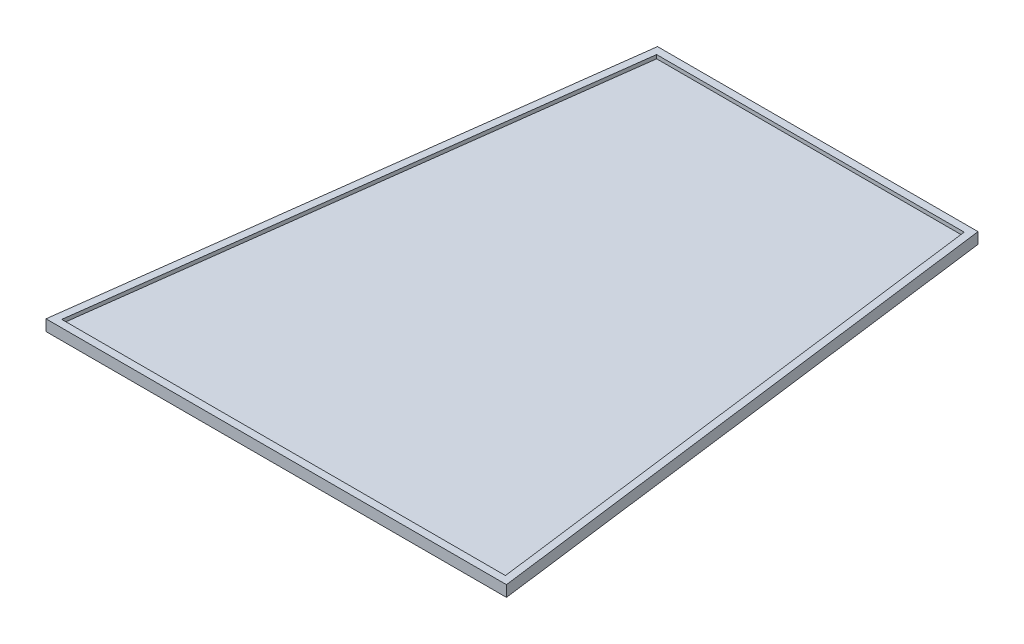
SolidWorks part; units mm, degrees
ref_plane "前视基准面" through (0, 0, 0) normal (0, 0, 1) x (1, 0, 0)
ref_plane "上视基准面" through (0, 0, 0) normal (0, 1, 0) x (1, 0, 0)
ref_plane "右视基准面" through (0, 0, 0) normal (1, 0, 0) x (0, 0, -1)
other "Configuration Table"
sketch "草图1" plane through (0, 0, 0) normal (0, 1, 0) x (1, 0, 0)
  line L0 (-31.25, 0) -> (31.25, 0)
  line L1 (31.25, 0) -> (21.75, 73.5)
  line L2 (21.75, 73.5) -> (-21.75, 73.5)
  line L3 (-21.75, 73.5) -> (-31.25, 0)
  point P3 (0, 73.5)
  dimension "D1" = 73.5
  dimension "D2" = 43.5
  dimension "D3" = 62.5
extrude "凸台-拉伸1" add sketch "草图1" along normal blind 1
sketch "草图2" plane through (0, 1, 0) normal (0, 1, 0) x (1, 0, 0)
  line L0 (-20.8709, 72.5) -> (-30.1124, 1)
  line L1 (-30.1124, 1) -> (30.1124, 1)
  line L2 (30.1124, 1) -> (20.8709, 72.5)
  line L3 (20.8709, 72.5) -> (-20.8709, 72.5)
  line L4 (-21.75, 73.5) -> (-31.25, 0)
  line L5 (-31.25, 0) -> (31.25, 0)
  line L6 (31.25, 0) -> (21.75, 73.5)
  line L7 (21.75, 73.5) -> (-21.75, 73.5)
  line L8 (-21.75, 73.5) -> (-31.25, 0)
  line L9 (-31.25, 0) -> (31.25, 0)
  line L10 (31.25, 0) -> (21.75, 73.5)
  line L11 (21.75, 73.5) -> (-21.75, 73.5)
  dimension "D1" = 0
  dimension "D2" = 1
extrude "凸台-拉伸2" add sketch "草图2" along normal blind 0.5
